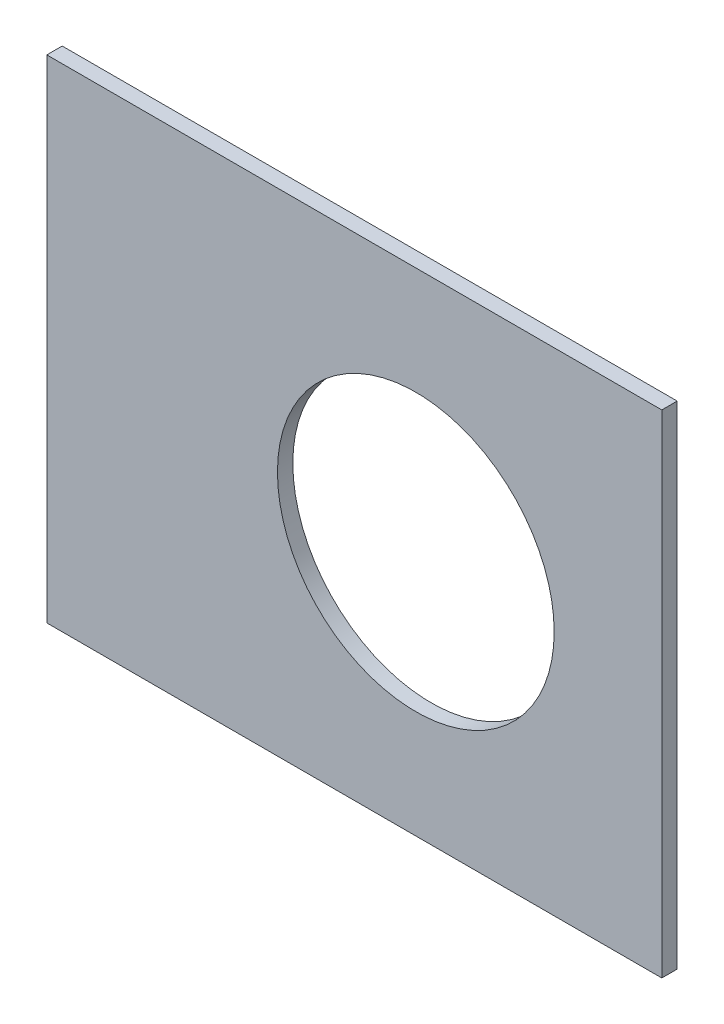
SolidWorks part; units mm, degrees
ref_plane "Front Plane" through (0, 0, 0) normal (0, 0, 1) x (1, 0, 0)
ref_plane "Top Plane" through (0, 0, 0) normal (0, 1, 0) x (1, 0, 0)
ref_plane "Right Plane" through (0, 0, 0) normal (1, 0, 0) x (0, 0, -1)
sketch "草图1" plane through (0, 0, 0) normal (0, 0, 1) x (1, 0, 0)
  line L0 (-20.1326, 80) -> (224.8397, 80) construction
  line L1 (0, 0) -> (200, 0)
  line L2 (0, 0) -> (0, 160)
  line L3 (0, 160) -> (200, 160)
  line L4 (200, 0) -> (200, 160)
  circle A0 centre (120, 80) radius 45
  point P7 (0, 80)
  point P8 (18, 80)
  point P9 (18, 80)
  dimension "D4" = 90
  dimension "D1" = 200
  dimension "D2" = 160
  dimension "D3" = 80
extrude "凸台-拉伸2" add sketch "草图1" along normal blind 5
